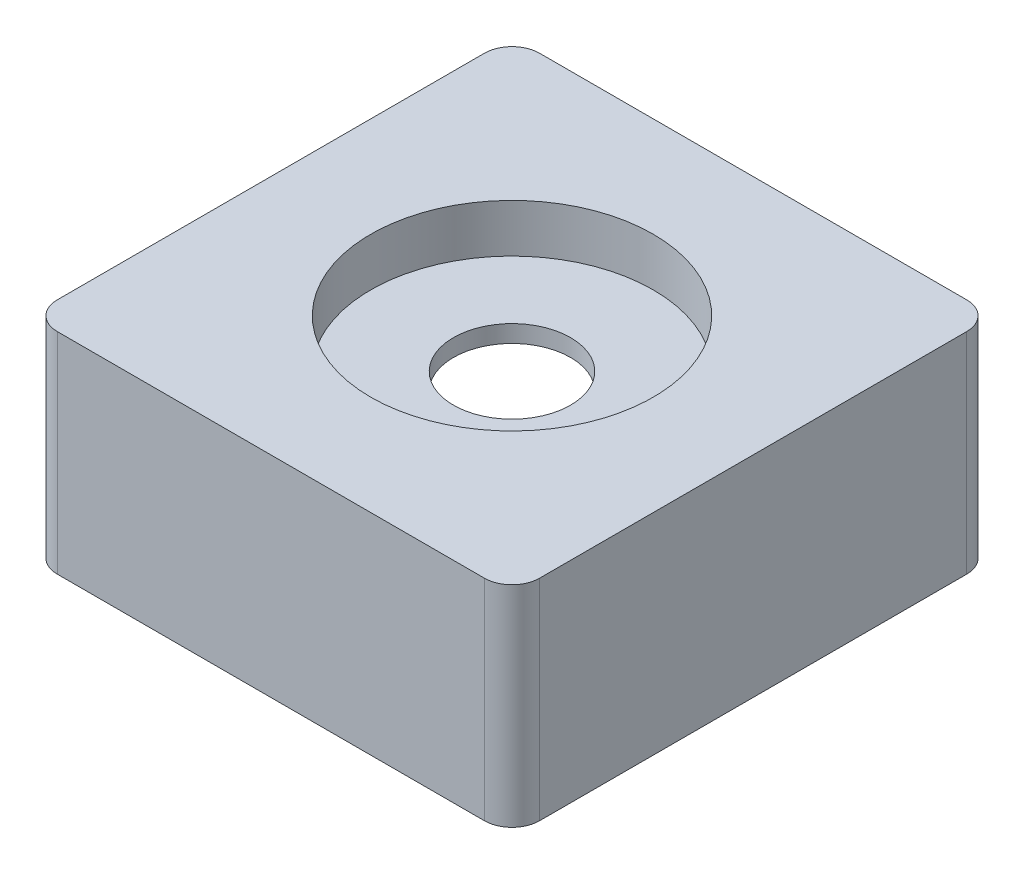
SolidWorks part; units mm, degrees
ref_plane "前视基准面" through (0, 0, 0) normal (0, 0, 1) x (1, 0, 0)
ref_plane "上视基准面" through (0, 0, 0) normal (0, 1, 0) x (1, 0, 0)
ref_plane "右视基准面" through (0, 0, 0) normal (1, 0, 0) x (0, 0, -1)
sketch "草图1" plane through (0, 0, 0) normal (0, 1, 0) x (1, 0, 0)
  line L1 (-70, 70) -> (70, 70)
  line L2 (-70, 70) -> (-70, -70)
  line L3 (-70, -70) -> (70, -70)
  line L4 (70, 70) -> (70, -70)
  line L5 (-70, 70) -> (70, -70) construction
  line L6 (-70, -70) -> (70, 70) construction
  circle A0 centre (0, 0) radius 41
extrude "凸台-拉伸1" add sketch "草图1" along normal blind 14
sketch "草图3" plane through (0, 0, 0) normal (0, -1, 0) x (1, 0, 0)
  line L1 (-70, 70) -> (70, 70)
  line L2 (-70, 70) -> (-70, -70)
  line L3 (-70, -70) -> (70, -70)
  line L4 (70, 70) -> (70, -70)
  line L5 (-70, 70) -> (70, -70) construction
  line L6 (-70, -70) -> (70, 70) construction
  circle A0 centre (0, 0) radius 17
  point P0 (0, 0)
extrude "凸台-拉伸2" add sketch "草图3" along normal blind 5
sketch "草图4" plane through (0, -5, 0) normal (0, -1, 0) x (1, 0, 0)
  line L1 (-70, 70) -> (70, 70)
  line L2 (-70, 70) -> (-70, -70)
  line L3 (-70, -70) -> (70, -70)
  line L4 (70, 70) -> (70, -70)
  line L5 (-70, 70) -> (70, -70) construction
  line L6 (-70, -70) -> (70, 70) construction
  line L7 (-60, 60) -> (60, 60)
  line L8 (-60, 60) -> (-60, -60)
  line L9 (-60, -60) -> (60, -60)
  line L10 (60, 60) -> (60, -60)
  line L11 (-60, 60) -> (60, -60) construction
  line L12 (-60, -60) -> (60, 60) construction
  point P0 (0, 0)
  point P6 (0, 0)
extrude "凸台-拉伸3" add sketch "草图4" along normal blind 42
fillet "圆角3" radius 8 4 edges at (-70, -16.5, 70) (-70, -16.5, -70) (70, -16.5, -70) (70, -16.5, 70)
sketch "草图5" plane through (-70, 0, 0) normal (-1, 0, 0) x (0, 0, 1)
  line L1 (62, -47) -> (-62, -47) construction
  line L3 (-10, -32) -> (-10, -47)
  line L5 (10, -32) -> (10, -47)
  line L8 (-10, -47) -> (10, -47)
  arc A1 (10, -32) -> (-10, -32) centre (0, -32) ccw
  point P3 (0, -47)
extrude "切除-拉伸1" cut sketch "草图5" against normal blind 6
